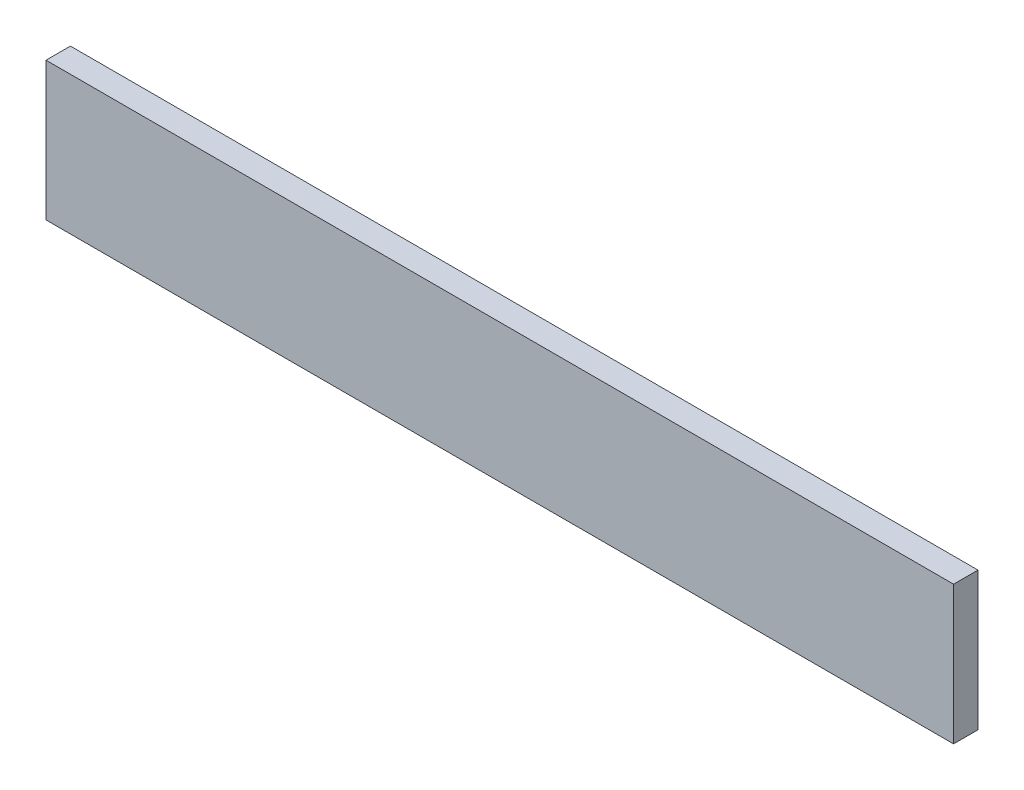
SolidWorks part; units mm, degrees
ref_plane "Ebene vorne" through (0, 0, 0) normal (0, 0, 1) x (1, 0, 0)
ref_plane "Ebene oben" through (0, 0, 0) normal (0, 1, 0) x (1, 0, 0)
ref_plane "Ebene rechts" through (0, 0, 0) normal (1, 0, 0) x (0, 0, -1)
sketch "Skizze1" plane through (0, 0, 0) normal (0, 0, 1) x (1, 0, 0)
  line L0 (-18.6182, 2.794) -> (18.542, 2.794)
  line L1 (18.542, 2.794) -> (18.542, -2.8702)
  line L2 (18.542, -2.8702) -> (-18.6182, -2.8702)
  line L3 (-18.6182, -2.8702) -> (-18.6182, 2.794)
extrude "Component_Outline" add sketch "Skizze1" along normal blind 1 separate body
sketch3d "3D-Skizze1"
  line L0 (0, 0, 0) -> (1, 0, 0)
  line L1 (0, 0, 0) -> (0, 1, 0)
  line L2 (0, 0, 0) -> (0, 0, 1)
  point P0 (0, 0, 0)
